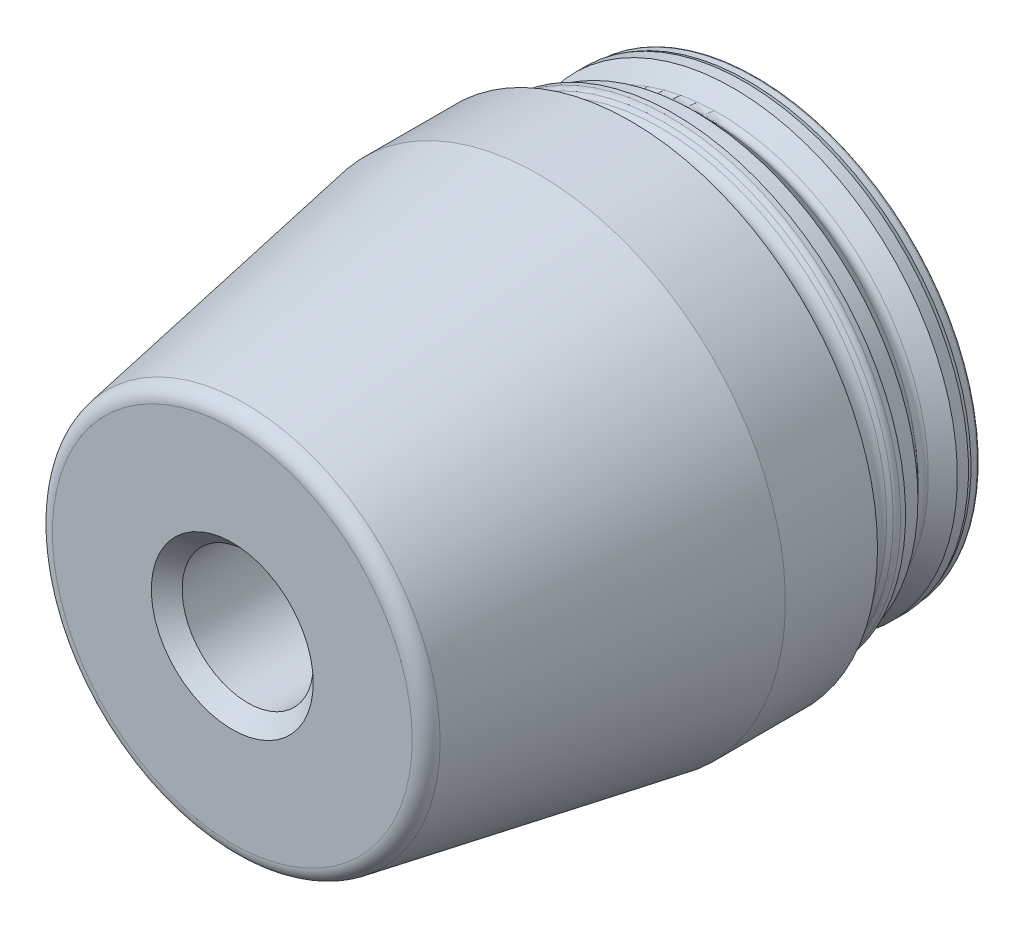
SolidWorks part; units mm, degrees
ref_plane "front" through (0, 0, 0) normal (0, 0, 1) x (1, 0, 0)
ref_plane "top" through (0, 0, 0) normal (0, 1, 0) x (1, 0, 0)
ref_plane "right" through (0, 0, 0) normal (1, 0, 0) x (0, 0, -1)
sketch "L2D-00 Layout" plane through (0, 0, 0) normal (1, 0, 0) x (0, 0, -1)
  line L1 (27.7667, 0) -> (-53.34, 0) construction
  line L2 (-13.9549, 25.4) -> (-45.466, 19.8437)
  line L3 (0, 23.0505) -> (2.032, 23.0505)
  line L4 (8.509, 22.6695) -> (8.509, 19.05)
  line L5 (-4.4764, 25.4) -> (-13.9549, 25.4)
  line L8 (-0.508, 23.8125) -> (0, 23.8125)
  line L9 (0, 23.8125) -> (0, 23.0505)
  line L10 (8.509, 19.05) -> (-7.366, 19.05)
  line L11 (-7.366, -19.05) -> (-12.1157, 0)
  line L12 (-3.3859, -23.5112) -> (-4.4764, -25.4)
  line L13 (6.096, -23.0505) -> (7.239, -23.0505)
  line L14 (3.5252, -21.5573) -> (2.032, -23.0505)
  line L15 (6.096, -23.0505) -> (4.6028, -21.5573)
  line L17 (-45.466, 19.8437) -> (-45.466, -19.8438)
  line L19 (-7.366, 19.05) -> (-12.1157, 0)
  line L20 (7.239, 23.0505) -> (7.62, 22.9235)
  line L21 (7.62, 22.9235) -> (8.255, 22.9235)
  line L22 (-1.0468, -23.5893) -> (-1.388, -23.2482)
  line L23 (7.62, -22.9235) -> (8.255, -22.9235)
  line L24 (7.239, -23.0505) -> (7.62, -22.9235)
  line L25 (8.509, -19.05) -> (-7.366, -19.05)
  line L26 (8.509, 19.05) -> (8.509, -19.05)
  line L28 (-1.0468, 23.5893) -> (-1.388, 23.2482)
  line L29 (6.096, 23.0505) -> (4.6028, 21.5573)
  line L30 (3.5252, 21.5573) -> (2.032, 23.0505)
  line L31 (6.096, 23.0505) -> (7.239, 23.0505)
  line L32 (0, -23.8125) -> (0, -23.0505)
  line L33 (-0.508, -23.8125) -> (0, -23.8125)
  line L34 (-4.4764, -25.4) -> (-13.9549, -25.4)
  line L35 (-3.3859, 23.5112) -> (-4.4764, 25.4)
  line L36 (8.509, -22.6695) -> (8.509, -19.05)
  line L37 (0, -23.0505) -> (2.032, -23.0505)
  line L39 (-13.9549, -25.4) -> (-45.466, -19.8438)
  arc A0 (4.6028, 21.5573) -> (3.5252, 21.5573) centre (4.064, 22.0961) cw
  circle A1 centre (4.064, -23.2672) radius 1.59 construction
  arc A2 (8.255, 22.9235) -> (8.509, 22.6695) centre (8.255, 22.6695) cw
  arc A3 (-0.508, 23.8125) -> (-1.0468, 23.5893) centre (-0.508, 23.0505) ccw
  arc A4 (-1.388, 23.2482) -> (-3.3859, 23.5112) centre (-2.286, 24.1462) cw
  circle A5 centre (4.064, 23.2672) radius 1.59 construction
  arc A6 (-1.388, -23.2482) -> (-3.3859, -23.5112) centre (-2.286, -24.1462) ccw
  arc A7 (-0.508, -23.8125) -> (-1.0468, -23.5893) centre (-0.508, -23.0505) cw
  arc A8 (8.255, -22.9235) -> (8.509, -22.6695) centre (8.255, -22.6695) ccw
  arc A9 (4.6028, -21.5573) -> (3.5252, -21.5573) centre (4.064, -22.0961) ccw
  point P48 (-45.466, 0)
  point P51 (4.064, 24.8572)
  point P63 (4.064, -24.8572)
  dimension "D2" = 50.8
  dimension "D26" = 45
  dimension "D29" = 0.762
  dimension "D30" = 1.27
  dimension "D3" = 0.254
  dimension "D5" = 46.101
  dimension "D8" = 8.509
  dimension "D32" = 0.762
  dimension "D33" = 1.27
  dimension "D36" = 3.1801
  dimension "D4" = 39.6875
  dimension "D6" = 53.975
  dimension "D7" = 0.762
  dimension "D9" = 76
  dimension "D10" = 31.5111
  dimension "D11" = 60
  dimension "D12" = 135
  dimension "D13" = 10
  dimension "D14" = 45.466
  dimension "D19" = 15.875
  dimension "D20" = 38.1
  dimension "D25" = 0.889
  dimension "D27" = 4.064
  dimension "D28" = 2.413
  dimension "D31" = 45.847
  dimension "D34" = 2.286
  dimension "D35" = 0.508
  dimension "D37" = 4.0005
  dimension "D38" = 49.7144
  dimension "D39" = 12.9854
sketch "Sketch3" plane through (0, 0, 0) normal (1, 0, 0) x (0, 0, -1)
  line L0 (27.7667, 0) -> (-53.34, 0) construction
  line L1 (-45.466, 19.8437) -> (-45.466, -19.8438) construction
  line L2 (-13.9549, 25.4) -> (-45.466, 19.8437) construction
  line L3 (-45.466, 19.8437) -> (-45.466, 0)
  line L4 (-13.9549, 25.4) -> (-45.466, 19.8437)
  line L8 (27.7667, 0) -> (-53.34, 0) construction
  line L11 (-4.4764, 25.4) -> (-13.9549, 25.4) construction
  line L12 (-3.3859, 23.5112) -> (-4.4764, 25.4) construction
  line L13 (-1.0468, 23.5893) -> (-1.388, 23.2482) construction
  line L14 (-0.508, 23.8125) -> (0, 23.8125) construction
  line L15 (0, 23.8125) -> (0, 23.0505) construction
  line L16 (0, 23.0505) -> (2.032, 23.0505) construction
  line L17 (3.5252, 21.5573) -> (2.032, 23.0505) construction
  line L18 (6.096, 23.0505) -> (4.6028, 21.5573) construction
  line L24 (6.096, 23.0505) -> (7.239, 23.0505) construction
  line L25 (7.239, 23.0505) -> (7.62, 22.9235) construction
  line L26 (7.62, 22.9235) -> (8.255, 22.9235) construction
  line L27 (8.509, 22.6695) -> (8.509, 19.05) construction
  line L28 (-7.366, 19.05) -> (-12.1157, 0) construction
  line L29 (8.509, 19.05) -> (-7.366, 19.05) construction
  line L30 (-45.466, 0) -> (-12.1157, 0)
  line L32 (-4.4764, 25.4) -> (-13.9549, 25.4)
  line L33 (-3.3859, 23.5112) -> (-4.4764, 25.4)
  line L34 (-1.0468, 23.5893) -> (-1.388, 23.2482)
  line L35 (-0.508, 23.8125) -> (0, 23.8125)
  line L36 (0, 23.8125) -> (0, 23.0505)
  line L37 (0, 23.0505) -> (2.032, 23.0505)
  line L38 (3.5252, 21.5573) -> (2.032, 23.0505)
  line L39 (6.096, 23.0505) -> (4.6028, 21.5573)
  line L40 (6.096, 23.0505) -> (7.239, 23.0505)
  line L41 (7.239, 23.0505) -> (7.62, 22.9235)
  line L42 (7.62, 22.9235) -> (8.255, 22.9235)
  line L43 (8.509, 22.6695) -> (8.509, 19.05)
  line L44 (-7.366, 19.05) -> (-12.1157, 0)
  line L45 (8.509, 19.05) -> (-7.366, 19.05)
  arc A1 (-3.3859, 23.5112) -> (-1.388, 23.2482) centre (-2.286, 24.1462) ccw construction
  arc A2 (-0.508, 23.8125) -> (-1.0468, 23.5893) centre (-0.508, 23.0505) ccw construction
  arc A3 (3.5252, 21.5573) -> (4.6028, 21.5573) centre (4.064, 22.0961) ccw construction
  arc A4 (8.509, 22.6695) -> (8.255, 22.9235) centre (8.255, 22.6695) ccw construction
  arc A5 (-3.3859, 23.5112) -> (-1.388, 23.2482) centre (-2.286, 24.1462) ccw
  arc A6 (-0.508, 23.8125) -> (-1.0468, 23.5893) centre (-0.508, 23.0505) ccw
  arc A7 (3.5252, 21.5573) -> (4.6028, 21.5573) centre (4.064, 22.0961) ccw
  arc A8 (8.509, 22.6695) -> (8.255, 22.9235) centre (8.255, 22.6695) ccw
revolve "FBR-00 Basic blank revolve." add sketch "Sketch3" angle 360 about L8
hole_wizard "5/8-11 Tapped Hole1" positions "3DSketch1" profile "Sketch20" tap size "5/8-11" standard "Ansi Inch"
sketch3d "3DSketch1"
  point P3 (0, 0, 45.466)
sketch "Sketch20" plane through (0, 0, 45.466) normal (1, 0, 0) x (0, -1, 0)
  line L0 (0, 0) -> (0, 44.1728)
  line L1 (0, 44.1728) -> (6.7462, 40.1193)
  line L2 (6.7462, 40.1193) -> (6.7462, 1.585)
  line L3 (6.7462, 1.585) -> (8.3312, 0)
  line L5 (8.3312, 0) -> (0, 0)
  line L6 (-6.7462, 1.585) -> (-8.3312, 0) construction
  line L10 (0, 44.1728) -> (-6.7462, 40.1193) construction
  line L11 (0, -6.35) -> (0, 107.95) construction
  dimension "Hole Dia." = 13.4925
  dimension "Hole Depth" = 40.1193
  dimension "Near C'Sink Dia." = 16.6624
  dimension "Near C'Sink Angle" = 90
  dimension "Drill Angle" = 118
chamfer "FCH-00 Chamfer 0.015" distance 0.381 angle 45
fillet "Fillet1" radius 1.5875
sketch "Sketch10" plane through (0, 0, 0) normal (0, 1, 0) x (1, 0, 0)
  line L0 (0, 38.5125) -> (0, -115.1189)
extrude "FCE-00 Section." [suppressed] cut sketch "Sketch10" against normal through all and the other way through all
sketch "mate point" plane through (0, 0, 45.466) normal (0, 0, 1) x (1, 0, 0)
  circle A0 centre (0, 0) radius 8.3312 construction
  point P0 (0, 0)
